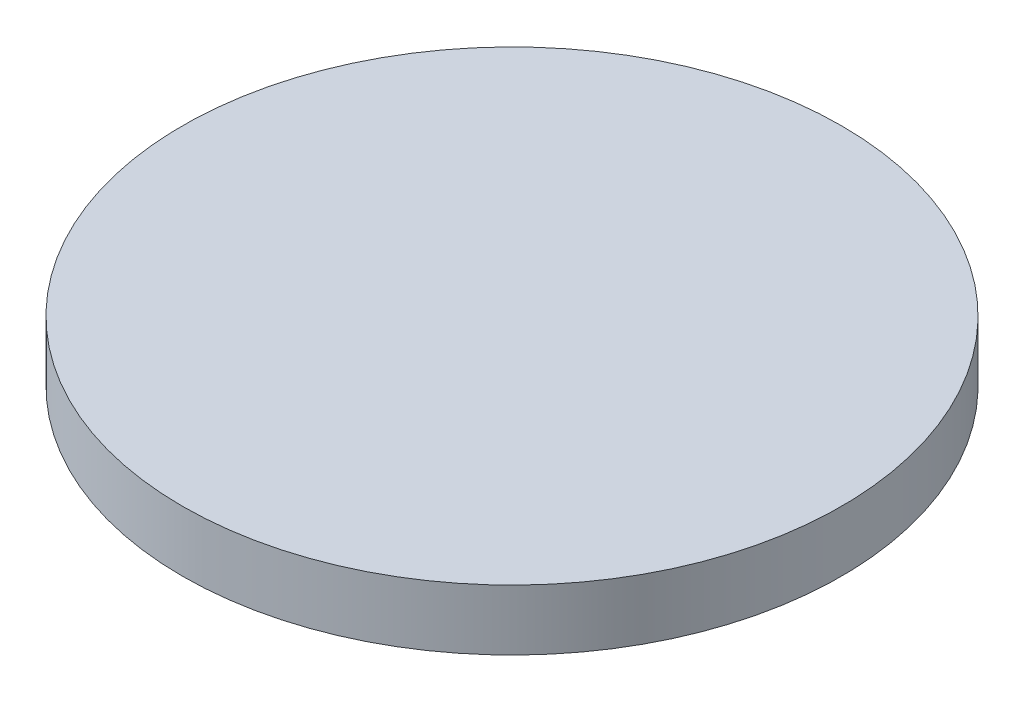
SolidWorks part; units mm, degrees
material "Nickel silver 65-12, UNS C75700"
ref_plane "Front Plane" through (0, 0, 0) normal (0, 0, 1) x (1, 0, 0)
ref_plane "Top Plane" through (0, 0, 0) normal (0, 1, 0) x (1, 0, 0)
ref_plane "Right Plane" through (0, 0, 0) normal (1, 0, 0) x (0, 0, -1)
sketch "Sketch2" plane through (0, 0, 0) normal (0, 1, 0) x (1, 0, 0)
  circle A0 centre (0, 0) radius 10.6045
  dimension "D1" = 21.209
extrude "Boss-Extrude1" add sketch "Sketch2" along normal blind 1.95
